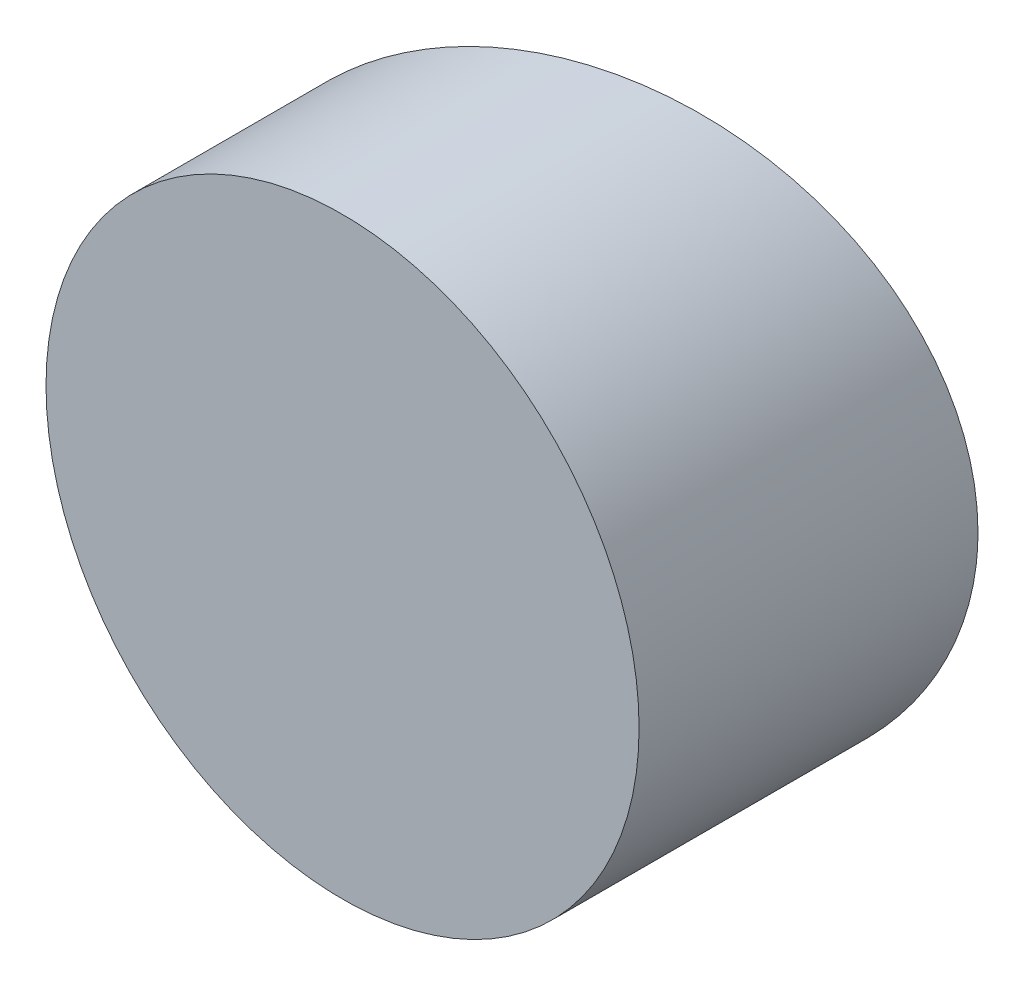
SolidWorks part; units mm, degrees
ref_plane "Front Plane" through (0, 0, 0) normal (0, 0, 1) x (1, 0, 0)
ref_plane "Top Plane" through (0, 0, 0) normal (0, 1, 0) x (1, 0, 0)
ref_plane "Right Plane" through (0, 0, 0) normal (1, 0, 0) x (0, 0, -1)
sketch "Sketch1" plane through (0, 0, 0) normal (0, 0, 1) x (1, 0, 0)
  circle A0 centre (1.6259, 0) radius 14
extrude "Boss-Extrude2" add sketch "Sketch1" along normal blind 16
ref_plane "Plane1" through (0, 14, 0) normal (0, 1, 0) x (1, 0, 0)
sketch "Sketch2" plane through (0, 14, 0) normal (0, 1, 0) x (1, 0, 0)
  line L5 (-12.3741, -8) -> (15.6259, 0)
  line L6 (-12.3741, 0) -> (-12.3741, -16) construction
  line L7 (15.6259, 0) -> (-12.3741, 0)
  line L8 (-12.3741, 0) -> (-12.3741, -8)
extrude "Cut-Extrude1" cut sketch "Sketch2" against normal blind 32
